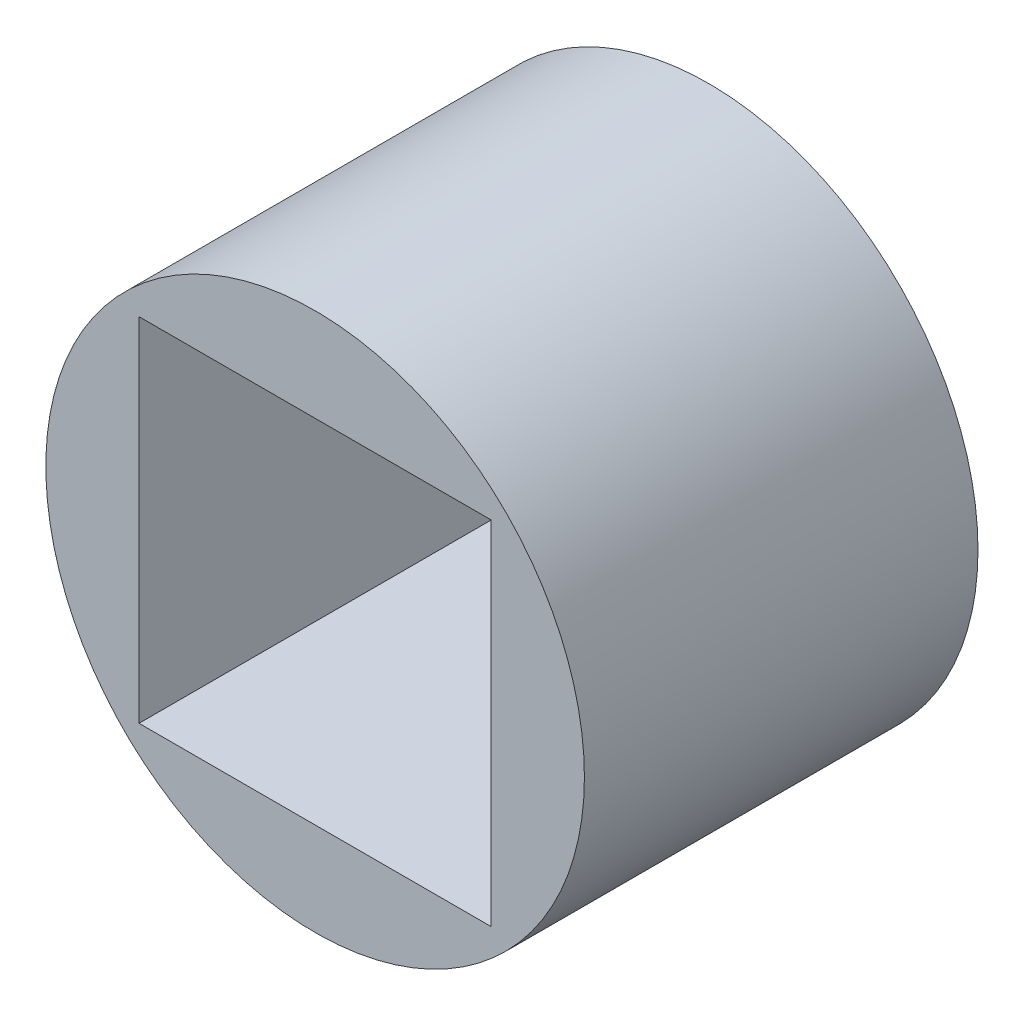
SolidWorks part; units mm, degrees
ref_plane "Front Plane" through (0, 0, 0) normal (0, 0, 1) x (1, 0, 0)
ref_plane "Top Plane" through (0, 0, 0) normal (0, 1, 0) x (1, 0, 0)
ref_plane "Right Plane" through (0, 0, 0) normal (1, 0, 0) x (0, 0, -1)
sketch "Sketch1" plane through (0, 0, 0) normal (0, 0, 1) x (1, 0, 0)
  circle A0 centre (0, 0) radius 13.25 construction
  circle A1 centre (0, 0) radius 13.25 construction
  circle A2 centre (0, 0) radius 13
  dimension "D1" = 26.5
  dimension "D2" = 0
  dimension "D3" = 0.25
extrude "Boss-Extrude1" add sketch "Sketch1" along normal blind 19
sketch "Sketch2" plane through (0, 0, 0) normal (0, 0, -1) x (-1, 0, 0)
  line L1 (-8.5, -8.5) -> (8.5, -8.5)
  line L2 (-8.5, -8.5) -> (-8.5, 8.5)
  line L3 (-8.5, 8.5) -> (8.5, 8.5)
  line L4 (8.5, -8.5) -> (8.5, 8.5)
  line L5 (-8.5, -8.5) -> (8.5, 8.5) construction
  line L6 (-8.5, 8.5) -> (8.5, -8.5) construction
  point P0 (0, 0)
  dimension "D1" = 17
  dimension "D2" = 17
extrude "Cut-Extrude1" cut sketch "Sketch2" against normal through all
sketch "Sketch3" plane through (0, 8.5, 0) normal (0, -1, 0) x (1, 0, 0)
  line L0 (-8.5018, 7.4231) -> (8.1138, 7.4231) construction
  text T0 "CSS-1" font "Impact" height in points 12
extrude "Cut-Extrude2" cut sketch "Sketch3" against normal blind 0.25
